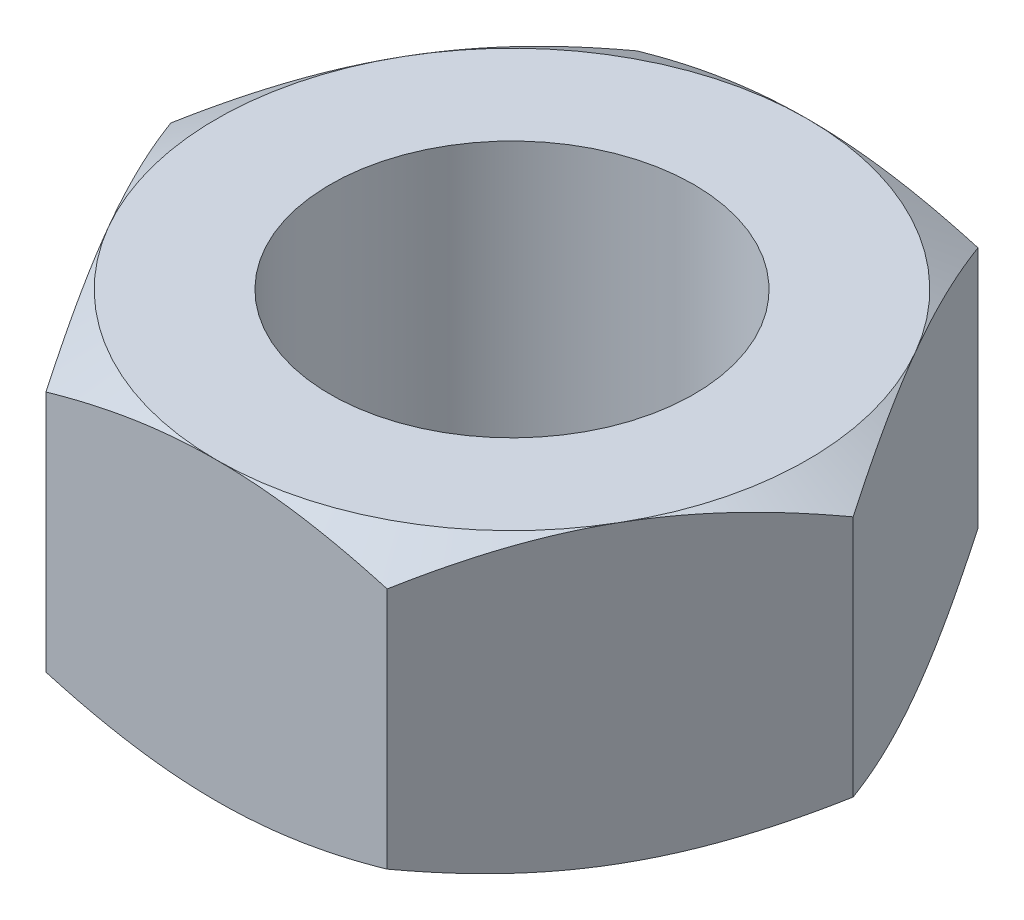
SolidWorks part; units mm, degrees
ref_plane "Front Plane" through (0, 0, 0) normal (0, 0, 1) x (1, 0, 0)
ref_plane "Top Plane" through (0, 0, 0) normal (0, 1, 0) x (1, 0, 0)
ref_plane "Right Plane" through (0, 0, 0) normal (1, 0, 0) x (0, 0, -1)
sketch "Sketch1" plane through (0, 0, 0) normal (0, 1, 0) x (1, 0, 0)
  line L1 (7.5056, 0) -> (3.7528, 6.5)
  line L2 (3.7528, 6.5) -> (-3.7528, 6.5)
  line L3 (-3.7528, 6.5) -> (-7.5056, 0)
  line L4 (-7.5056, 0) -> (-3.7528, -6.5)
  line L5 (-3.7528, -6.5) -> (3.7528, -6.5)
  line L6 (3.7528, -6.5) -> (7.5056, 0)
  circle A0 centre (0, 0) radius 6.5 construction
  circle A1 centre (0, 0) radius 4
  dimension "D1" = 13
  dimension "D2" = 8
extrude "Boss-Extrude1" add sketch "Sketch1" along normal mid plane 6.5 contours L5 L6 L1 L2 L3 L4 A1
sketch "Sketch2" plane through (0, 3.25, 0) normal (0, 1, 0) x (1, 0, 0)
  circle A0 centre (0, 0) radius 6.5
  circle A1 centre (0, 0) radius 6.5 construction
extrude "Cut-Extrude1" cut sketch "Sketch2" against normal through all draft 60 flip side to cut
mirror "Mirror1" about plane through (0, 0, 0) normal (0, 1, 0) of "Cut-Extrude1"
